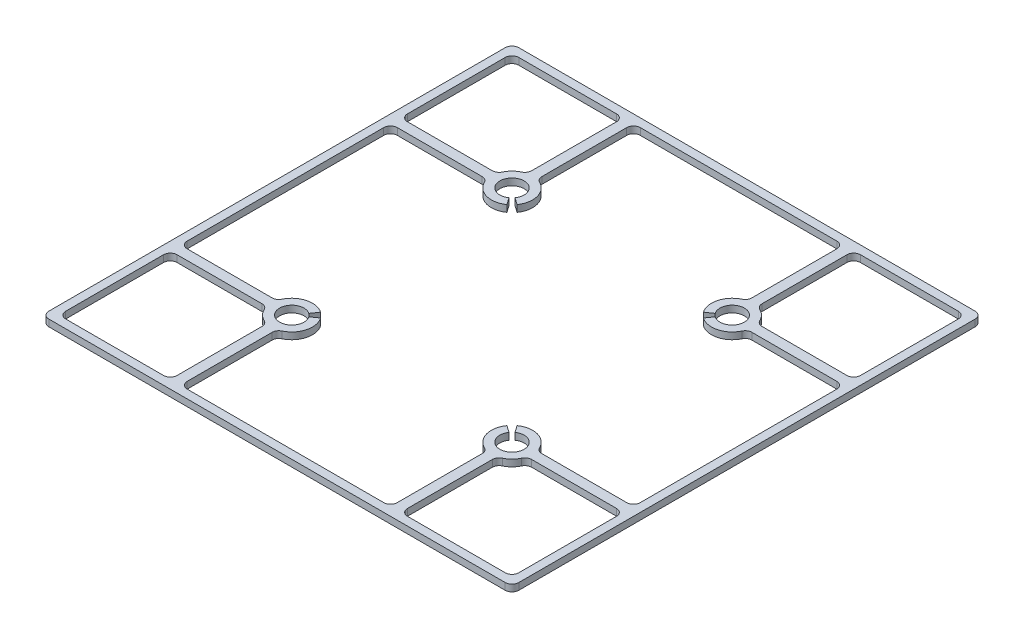
SolidWorks part; units mm, degrees
ref_plane "Front Plane" through (0, 0, 0) normal (0, 0, 1) x (1, 0, 0)
ref_plane "Top Plane" through (0, 0, 0) normal (0, 1, 0) x (1, 0, 0)
ref_plane "Right Plane" through (0, 0, 0) normal (1, 0, 0) x (0, 0, -1)
sketch "Sketch1" plane through (0, 0, 0) normal (0, 1, 0) x (1, 0, 0)
  line L0 (0, 7.62) -> (0, -6.6178) construction
  line L1 (-58.1134, -58.1134) -> (-58.1134, 58.1134) construction
  line L2 (-78.1134, -78.1134) -> (78.1134, -78.1134) construction
  line L3 (-78.1134, -78.1134) -> (-78.1134, 78.1134) construction
  line L4 (-78.1134, 78.1134) -> (78.1134, 78.1134) construction
  line L5 (78.1134, -78.1134) -> (78.1134, 78.1134) construction
  line L6 (-78.1134, -78.1134) -> (78.1134, 78.1134) construction
  line L7 (-78.1134, 78.1134) -> (78.1134, -78.1134) construction
  line L8 (-58.1134, 58.1134) -> (58.1134, 58.1134) construction
  line L9 (58.1134, -58.1134) -> (58.1134, 58.1134) construction
  line L10 (-58.1134, -58.1134) -> (58.1134, -58.1134) construction
  line L11 (-68.1134, -68.1134) -> (-68.1134, 68.1134) construction
  line L12 (-58.1134, -32.5) -> (-58.1134, 32.5) construction
  line L13 (32.5, 32.5) -> (-32.5, -32.5) construction
  line L14 (58.1134, 32.5) -> (58.1134, -32.5) construction
  line L15 (-68.1134, 68.1134) -> (68.1134, 68.1134) construction
  line L16 (32.5, -32.5) -> (-32.5, 32.5) construction
  line L17 (-61.7191, 0) -> (55.7541, 0) construction
  line L18 (-32.5, 58.1134) -> (32.5, 58.1134) construction
  line L19 (32.5, -58.1134) -> (-32.5, -58.1134) construction
  line L20 (0, 76.2002) -> (0, -66.1781) construction
  line L21 (68.1134, -68.1134) -> (68.1134, 68.1134) construction
  line L22 (-68.1134, -68.1134) -> (68.1134, -68.1134) construction
  line L23 (69.3634, -67.3634) -> (69.3634, 67.3634)
  line L24 (-67.3634, 69.3634) -> (67.3634, 69.3634)
  line L25 (-69.3634, -67.3634) -> (-69.3634, 67.3634)
  line L26 (-67.3634, -69.3634) -> (67.3634, -69.3634)
  line L27 (66.8634, -64.8634) -> (66.8634, -35.9957)
  line L28 (-64.8634, 66.8634) -> (-36, 66.8634)
  line L29 (-66.8634, -64.8634) -> (-66.8634, -35.9957)
  line L30 (-64.8634, -66.8634) -> (-36, -66.8634)
  line L31 (36, 66.8634) -> (64.8634, 66.8634)
  line L32 (-32.5, 36.1) -> (-32.5, 58.1134) construction
  line L33 (-30.4351, 29.5511) -> (-29.0012, 27.5032)
  line L34 (-29.5511, 30.4351) -> (-27.5032, 29.0012)
  line L35 (-31, 39.8048) -> (-31, 64.8634)
  line L36 (-34, 39.8048) -> (-34, 64.8634)
  line L37 (-34, 36.1) -> (-34, 66.8634) construction
  line L38 (-31, 36.1) -> (-31, 66.8634) construction
  line L39 (-29, 66.8634) -> (29, 66.8634)
  line L40 (-66.8634, 66.8634) -> (66.8634, 66.8634) construction
  line L41 (-32.5, 36.1) -> (-32.5, 66.8634) construction
  line L42 (-39.8069, 33.9957) -> (-64.8634, 33.9957)
  line L43 (-39.8069, 31.0043) -> (-64.8634, 31.0043)
  line L44 (66.8634, 35.9957) -> (66.8634, 64.8634)
  line L45 (66.8634, -66.8634) -> (66.8634, 66.8634) construction
  line L46 (-66.8634, 35.9957) -> (-66.8634, 64.8634)
  line L47 (-66.8634, -66.8634) -> (-66.8634, 66.8634) construction
  line L48 (30.4351, 29.5511) -> (29.0012, 27.5032)
  line L49 (29.5511, 30.4351) -> (27.5032, 29.0012)
  line L50 (39.8069, 31.0043) -> (64.8634, 31.0043)
  line L51 (39.8069, 33.9957) -> (64.8634, 33.9957)
  line L52 (31, 39.8048) -> (31, 64.8634)
  line L53 (34, 39.8048) -> (34, 64.8634)
  line L54 (-34, -39.8048) -> (-34, -64.8634)
  line L55 (-31, -39.8048) -> (-31, -64.8634)
  line L56 (-29.5511, -30.4351) -> (-27.5032, -29.0012)
  line L57 (-30.4351, -29.5511) -> (-29.0012, -27.5032)
  line L58 (-39.8069, -31.0043) -> (-64.8634, -31.0043)
  line L59 (-39.8069, -33.9957) -> (-64.8634, -33.9957)
  line L60 (31, -39.8048) -> (31, -64.8634)
  line L61 (34, -39.8048) -> (34, -64.8634)
  line L62 (29.5511, -30.4351) -> (27.5032, -29.0012)
  line L63 (30.4351, -29.5511) -> (29.0012, -27.5032)
  line L64 (39.8069, -33.9957) -> (64.8634, -33.9957)
  line L65 (39.8069, -31.0043) -> (64.8634, -31.0043)
  line L66 (66.8634, -29.0043) -> (66.8634, 29.0043)
  line L67 (-66.8634, -29.0043) -> (-66.8634, 29.0043)
  line L68 (36, -66.8634) -> (64.8634, -66.8634)
  line L69 (-66.8634, -66.8634) -> (66.8634, -66.8634) construction
  line L70 (-29, -66.8634) -> (29, -66.8634)
  line L71 (-69.3634, -69.3634) -> (-69.3634, 69.3634) construction
  line L72 (-69.3634, 69.3634) -> (69.3634, 69.3634) construction
  line L73 (-69.3634, -69.3634) -> (69.3634, -69.3634) construction
  line L74 (69.3634, -69.3634) -> (69.3634, 69.3634) construction
  arc A0 (-27.5032, 29.0012) -> (-29.8642, 38.0011) centre (-32.5, 32.5) ccw
  arc A1 (-35.1358, 38.0011) -> (-38.0027, 35.1326) centre (-32.5, 32.5) ccw
  arc A2 (-38.0027, 29.8674) -> (-29.0012, 27.5032) centre (-32.5, 32.5) ccw
  arc A3 (27.5032, 29.0012) -> (29.8642, 38.0011) centre (32.5, 32.5) cw
  arc A4 (29.5511, 30.4351) -> (30.4351, 29.5511) centre (32.5, 32.5) cw
  arc A5 (38.0027, 29.8674) -> (29.0012, 27.5032) centre (32.5, 32.5) cw
  arc A6 (35.1358, 38.0011) -> (38.0027, 35.1326) centre (32.5, 32.5) cw
  arc A7 (-27.5032, -29.0012) -> (-29.8642, -38.0011) centre (-32.5, -32.5) cw
  arc A8 (-29.5511, -30.4351) -> (-30.4351, -29.5511) centre (-32.5, -32.5) cw
  arc A9 (-35.1358, -38.0011) -> (-38.0027, -35.1326) centre (-32.5, -32.5) cw
  arc A10 (-38.0027, -29.8674) -> (-29.0012, -27.5032) centre (-32.5, -32.5) cw
  arc A11 (35.1358, -38.0011) -> (38.0027, -35.1326) centre (32.5, -32.5) ccw
  arc A12 (-32.5, -58.1134) -> (-58.1134, -32.5) centre (-32.5, -32.5) cw construction
  arc A13 (-29.5511, 30.4351) -> (-30.4351, 29.5511) centre (-32.5, 32.5) ccw
  arc A14 (27.5032, -29.0012) -> (29.8642, -38.0011) centre (32.5, -32.5) ccw
  arc A15 (29.5511, -30.4351) -> (30.4351, -29.5511) centre (32.5, -32.5) ccw
  arc A16 (32.5, 58.1134) -> (58.1134, 32.5) centre (32.5, 32.5) cw construction
  arc A17 (38.0027, -29.8674) -> (29.0012, -27.5032) centre (32.5, -32.5) ccw
  arc A18 (32.5, -58.1134) -> (58.1134, -32.5) centre (32.5, -32.5) ccw construction
  arc A19 (-69.3634, 67.3634) -> (-67.3634, 69.3634) centre (-67.3634, 67.3634) cw
  arc A20 (-64.8634, 66.8634) -> (-66.8634, 64.8634) centre (-64.8634, 64.8634) ccw
  arc A21 (-32.5, 58.1134) -> (-58.1134, 32.5) centre (-32.5, 32.5) ccw construction
  arc A22 (-34, 64.8634) -> (-36, 66.8634) centre (-36, 64.8634) ccw
  arc A23 (-29, 66.8634) -> (-31, 64.8634) centre (-29, 64.8634) ccw
  arc A24 (-38.0027, 35.1326) -> (-39.8069, 33.9957) centre (-39.8069, 35.9957) cw
  arc A25 (-35.1358, 38.0011) -> (-34, 39.8048) centre (-36, 39.8048) ccw
  arc A26 (-29.8642, 38.0011) -> (-31, 39.8048) centre (-29, 39.8048) cw
  arc A27 (-38.0027, 29.8674) -> (-39.8069, 31.0043) centre (-39.8069, 29.0043) ccw
  arc A28 (-64.8634, 33.9957) -> (-66.8634, 35.9957) centre (-64.8634, 35.9957) cw
  arc A29 (-66.8634, 29.0043) -> (-64.8634, 31.0043) centre (-64.8634, 29.0043) cw
  arc A30 (-66.8634, -29.0043) -> (-64.8634, -31.0043) centre (-64.8634, -29.0043) ccw
  arc A31 (-66.8634, -35.9957) -> (-64.8634, -33.9957) centre (-64.8634, -35.9957) cw
  arc A32 (-38.0027, -29.8674) -> (-39.8069, -31.0043) centre (-39.8069, -29.0043) cw
  arc A33 (-38.0027, -35.1326) -> (-39.8069, -33.9957) centre (-39.8069, -35.9957) ccw
  arc A34 (-34, -39.8048) -> (-35.1358, -38.0011) centre (-36, -39.8048) ccw
  arc A35 (-29.8642, -38.0011) -> (-31, -39.8048) centre (-29, -39.8048) ccw
  arc A36 (-69.3634, -67.3634) -> (-67.3634, -69.3634) centre (-67.3634, -67.3634) ccw
  arc A37 (-64.8634, -66.8634) -> (-66.8634, -64.8634) centre (-64.8634, -64.8634) cw
  arc A38 (-36, -66.8634) -> (-34, -64.8634) centre (-36, -64.8634) ccw
  arc A39 (-31, -64.8634) -> (-29, -66.8634) centre (-29, -64.8634) ccw
  arc A40 (29, -66.8634) -> (31, -64.8634) centre (29, -64.8634) ccw
  arc A41 (36, -66.8634) -> (34, -64.8634) centre (36, -64.8634) cw
  arc A42 (31, -39.8048) -> (29.8642, -38.0011) centre (29, -39.8048) ccw
  arc A43 (34, -39.8048) -> (35.1358, -38.0011) centre (36, -39.8048) cw
  arc A44 (38.0027, -35.1326) -> (39.8069, -33.9957) centre (39.8069, -35.9957) cw
  arc A45 (38.0027, -29.8674) -> (39.8069, -31.0043) centre (39.8069, -29.0043) ccw
  arc A46 (66.8634, -29.0043) -> (64.8634, -31.0043) centre (64.8634, -29.0043) cw
  arc A47 (66.8634, -35.9957) -> (64.8634, -33.9957) centre (64.8634, -35.9957) ccw
  arc A48 (66.8634, -64.8634) -> (64.8634, -66.8634) centre (64.8634, -64.8634) cw
  arc A49 (69.3634, -67.3634) -> (67.3634, -69.3634) centre (67.3634, -67.3634) cw
  arc A50 (66.8634, 35.9957) -> (64.8634, 33.9957) centre (64.8634, 35.9957) cw
  arc A51 (66.8634, 29.0043) -> (64.8634, 31.0043) centre (64.8634, 29.0043) ccw
  arc A52 (38.0027, 35.1326) -> (39.8069, 33.9957) centre (39.8069, 35.9957) ccw
  arc A53 (38.0027, 29.8674) -> (39.8069, 31.0043) centre (39.8069, 29.0043) cw
  arc A54 (35.1358, 38.0011) -> (34, 39.8048) centre (36, 39.8048) cw
  arc A55 (29.8642, 38.0011) -> (31, 39.8048) centre (29, 39.8048) ccw
  arc A56 (31, 64.8634) -> (29, 66.8634) centre (29, 64.8634) ccw
  arc A57 (36, 66.8634) -> (34, 64.8634) centre (36, 64.8634) ccw
  arc A58 (66.8634, 64.8634) -> (64.8634, 66.8634) centre (64.8634, 64.8634) ccw
  arc A59 (69.3634, 67.3634) -> (67.3634, 69.3634) centre (67.3634, 67.3634) ccw
  point P0 (0, 0)
  point P52 (32.5, 32.5)
  point P53 (-32.5, 32.5)
  point P54 (-32.5, -32.5)
  point P55 (32.5, -32.5)
  point P76 (-32.5, 58.1134)
  point P77 (-56.4, 32.5)
  point P78 (-58.1134, -32.5)
  point P79 (-32.5, -58.1134)
  point P80 (32.5, -58.1134)
  point P81 (58.1134, -32.5)
  point P117 (-38.4138, 33.9957)
  point P120 (-34, 38.4127)
  point P123 (-31, 38.4127)
  point P126 (-38.4138, 31.0043)
  point P129 (-66.8634, 33.9957)
  point P132 (-66.8634, 31.0043)
  point P135 (-66.8634, -31.0043)
  point P138 (-66.8634, -33.9957)
  point P141 (-38.4138, -31.0043)
  point P144 (-38.4138, -33.9957)
  point P147 (-34, -38.4127)
  point P150 (-31, -38.4127)
  point P163 (31, -66.8634)
  point P166 (34, -66.8634)
  point P169 (31, -38.4127)
  point P172 (34, -38.4127)
  point P175 (38.4138, -33.9957)
  point P178 (38.4138, -31.0043)
  point P181 (66.8634, -31.0043)
  point P184 (66.8634, -33.9957)
  point P193 (66.8634, 33.9957)
  point P196 (66.8634, 31.0043)
  point P199 (38.4138, 33.9957)
  point P202 (38.4138, 31.0043)
  point P205 (34, 38.4127)
  point P208 (31, 38.4127)
  point P211 (31, 66.8634)
  point P214 (34, 66.8634)
  dimension "D1" = 65
  dimension "D2" = 2
  dimension "D8" = 2.5
  dimension "D9" = 7.2
  dimension "D14" = 2
  dimension "D15" = 2
  dimension "D16" = 2
  dimension "D17" = 2
  dimension "D18" = 2
  dimension "D19" = 2
  dimension "D20" = 2
  dimension "D21" = 2
  dimension "D22" = 2
  dimension "D23" = 2
  dimension "D24" = 2
  dimension "D25" = 2
  dimension "D26" = 2
  dimension "D27" = 2
  dimension "D28" = 2
  dimension "D29" = 2
  dimension "D30" = 2
  dimension "D31" = 2
  dimension "D32" = 2
  dimension "D33" = 2
  dimension "D34" = 2
  dimension "D35" = 2
  dimension "D36" = 2
  dimension "D37" = 2
  dimension "D38" = 2
  dimension "D39" = 2
  dimension "D40" = 2
  dimension "D41" = 2
  dimension "D42" = 2
  dimension "D43" = 2
  dimension "D44" = 2
  dimension "D45" = 2
  dimension "D46" = 2
  dimension "D47" = 2
  dimension "D48" = 2
  dimension "D49" = 2
  dimension "D50" = 2
  dimension "D51" = 2
  dimension "D52" = 2
  dimension "D3" = 32.5
  dimension "D4" = 20
  dimension "D5" = 20
  dimension "D6" = 1.25
  dimension "D10" = 10
  dimension "D11" = 20
  dimension "D7" = 1.25
  dimension "D12" = 1.5
  dimension "D13" = 1.5
extrude "Boss-Extrude2" add sketch "Sketch1" along normal blind 2
